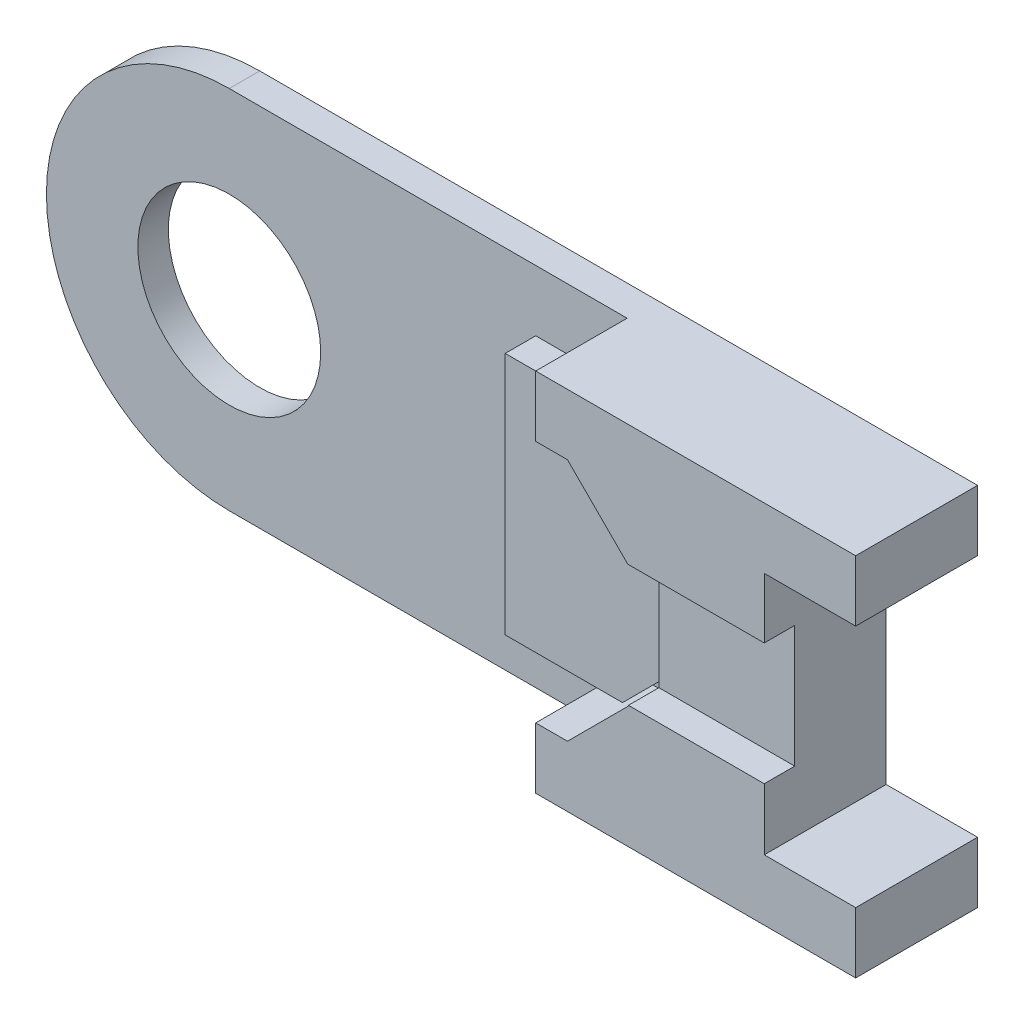
SolidWorks part; units mm, degrees
ref_plane "Front Plane" through (0, 0, 0) normal (0, 0, 1) x (1, 0, 0)
ref_plane "Top Plane" through (0, 0, 0) normal (0, 1, 0) x (1, 0, 0)
ref_plane "Right Plane" through (0, 0, 0) normal (1, 0, 0) x (0, 0, -1)
sketch "Sketch2" plane through (0, 0, 0) normal (0, 0, 1) x (1, 0, 0)
  line L0 (46.207, 120) -> (-84.3434, 120)
  line L1 (0, 0) -> (151.207, 0)
  line L3 (46.207, 120) -> (151.207, 120)
  line L4 (151.207, 0) -> (151.207, 120)
  line L7 (0, 0) -> (-84.3434, 0)
  arc A2 (-84.3434, 120) -> (-84.3434, 0) centre (-84.3434, 60) ccw
  circle A3 centre (-84.3434, 60) radius 30
  point P4 (52.5, 50)
  dimension "D1" = 60
  dimension "D2" = 120
extrude "Boss-Extrude2" add sketch "Sketch2" along normal blind 10
sketch "Sketch4" plane through (151.207, 0, 0) normal (1, 0, 0) x (0, 0, -1)
  line L0 (-10, 120) -> (0, 120) construction
  line L1 (-21.2953, 100) -> (18.4488, 100)
  line L2 (-21.2953, 100) -> (-21.2953, 20)
  line L3 (-21.2953, 20) -> (18.4488, 20)
  line L4 (18.4488, 100) -> (18.4488, 20)
  line L5 (-21.2953, 100) -> (18.4488, 20) construction
  line L6 (-21.2953, 20) -> (18.4488, 100) construction
  point P4 (-1.4233, 60)
  point P7 (-5, 120)
  dimension "D1" = 80
  dimension "D2" = 20
extrude "Cut-Extrude1" cut sketch "Sketch4" against normal blind 30
sketch "Sketch5" plane through (0, 0, 0) normal (0, 0, 1) x (1, 0, 0)
  line L0 (-84.3434, 0) -> (151.207, 0) construction
  line L1 (151.207, 120) -> (46.207, 120)
  line L2 (151.207, 120) -> (151.207, 0)
  line L3 (151.207, 0) -> (46.207, 0)
  line L4 (46.207, 120) -> (46.207, 0)
  line L5 (151.207, 120) -> (46.207, 0) construction
  line L6 (151.207, 0) -> (46.207, 120) construction
  point P4 (98.707, 60)
  dimension "D1" = 105
extrude "Boss-Extrude3" add sketch "Sketch5" along normal blind 40
sketch "Sketch6" plane through (151.207, 0, 0) normal (1, 0, 0) x (0, 0, -1)
  line L0 (-40, 120) -> (0, 120) construction
  line L1 (-55.9859, 100) -> (22.1204, 100)
  line L2 (-55.9859, 100) -> (-55.9859, 20)
  line L3 (-55.9859, 20) -> (22.1204, 20)
  line L4 (22.1204, 100) -> (22.1204, 20)
  line L5 (-55.9859, 100) -> (22.1204, 20) construction
  line L6 (-55.9859, 20) -> (22.1204, 100) construction
  point P4 (-16.9327, 60)
  dimension "D1" = 80
  dimension "D2" = 20
extrude "Cut-Extrude2" cut sketch "Sketch6" against normal blind 30
sketch "Sketch7" plane through (0, 0, 40) normal (0, 0, 1) x (1, 0, 0)
  line L1 (121.5427, 80.2091) -> (76.5427, 80.2091)
  line L2 (121.5427, 80.2091) -> (121.5427, 40.2091)
  line L3 (121.5427, 40.2091) -> (76.5427, 40.2091)
  line L4 (76.5427, 80.2091) -> (76.5427, 40.2091)
  line L5 (121.5427, 80.2091) -> (76.5427, 40.2091) construction
  line L6 (121.5427, 40.2091) -> (76.5427, 80.2091) construction
  point P4 (99.0427, 60.2091)
  dimension "D1" = 40
  dimension "D2" = 45
extrude "Cut-Extrude3" cut sketch "Sketch7" against normal blind 10
sketch "Sketch8" plane through (0, 0, 40) normal (0, 0, 1) x (1, 0, 0)
  line L0 (151.207, 120) -> (46.207, 120) construction
  line L1 (19.5991, 100) -> (56.6336, 100)
  line L2 (19.5991, 100) -> (19.5991, 20)
  line L3 (56.6336, 100) -> (76.6336, 80)
  line L4 (56.6336, 20) -> (76.6336, 40)
  line L10 (19.5991, 20) -> (56.6336, 20)
  line L11 (76.6336, 80) -> (76.6336, 40)
  line L13 (19.5991, 100) -> (76.6336, 20) construction
  line L14 (19.5991, 20) -> (76.6336, 100) construction
  line L15 (46.207, 0) -> (151.207, 0) construction
  point P2 (0, 0)
  point P5 (0, 0)
  point P6 (48.1164, 60)
  point P16 (46.32, 60)
  dimension "D1" = 20
  dimension "D2" = 20
extrude "Cut-Extrude4" cut sketch "Sketch8" against normal blind 30
sketch "Sketch9" plane through (0, 0, 10) normal (0, 0, 1) x (1, 0, 0)
  line L0 (46.207, 100) -> (16.207, 100)
  line L1 (16.207, 100) -> (16.207, 20)
  line L2 (16.207, 20) -> (46.207, 20)
  line L3 (46.207, 20) -> (54.6934, 20)
  line L4 (54.6934, 20) -> (76.6336, 41.9402)
  line L5 (76.6336, 40) -> (76.6336, 80) construction
  line L6 (76.6336, 41.9402) -> (76.6336, 80)
  line L7 (76.6336, 80) -> (56.6336, 100) construction
  line L8 (76.6336, 80) -> (56.6336, 100)
  line L9 (56.6336, 100) -> (46.207, 100) construction
  line L10 (56.6336, 100) -> (46.207, 100)
  line L11 (46.207, 20) -> (56.6336, 20) construction
  line L12 (46.207, 120) -> (46.207, 100) construction
  point P3 (54.6934, 20)
  dimension "D1" = 30
extrude "Boss-Extrude4" add sketch "Sketch9" along normal blind 10
